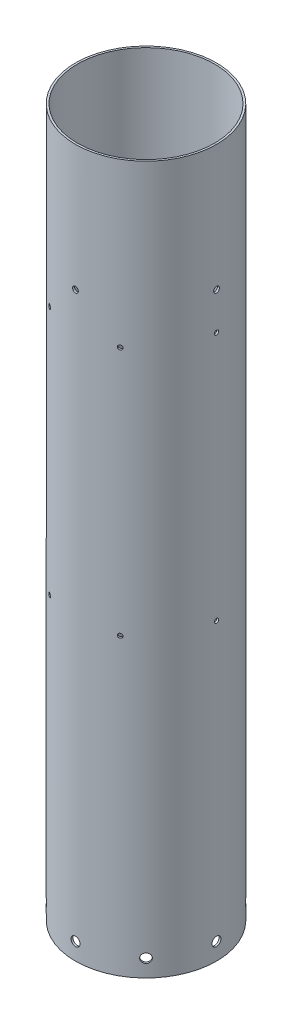
SolidWorks part; units mm, degrees
material "A-Glass Fiber"
ref_plane "Front Plane" through (0, 0, 0) normal (0, 0, 1) x (1, 0, 0)
ref_plane "Top Plane" through (0, 0, 0) normal (0, 1, 0) x (1, 0, 0)
ref_plane "Right Plane" through (0, 0, 0) normal (1, 0, 0) x (0, 0, -1)
sketch "Sketch2" plane through (0, 0, 0) normal (0, 1, 0) x (1, 0, 0)
  circle A0 centre (0, 0) radius 76.2
  circle A1 centre (0, 0) radius 78.359
  dimension "D1" = 156.718
  dimension "D2" = 2.159
extrude "Boss-Extrude1" add sketch "Sketch2" along normal blind 785.495
sketch "Sketch3" plane through (0, 127, 0) normal (1, 0, 0) x (0, 0, -1)
  circle A0 centre (0, -44.45) radius 4.7625 construction
  circle A1 centre (0, -44.45) radius 4.7625 construction
  circle A2 centre (0, -44.45) radius 5.0165
  dimension "D1" = 0.254
extrude "LOX to Kero, LOX Side Holes" [suppressed] cut sketch "Sketch3" along normal up to surface (76.0347 mm away)
pattern_circular "CirPattern1" [suppressed] count 8 over 360
sketch "Sketch4" plane through (0, -25.4, 0) normal (1, 0, 0) x (0, 0, 1)
  circle A0 centre (0, -44.45) radius 4.7625 construction
  circle A1 centre (0, -44.45) radius 4.7625 construction
  circle A2 centre (0, -44.45) radius 5.0165
  dimension "D1" = 0.254
extrude "LOX to Kero, Kero Side Holes" [suppressed] cut sketch "Sketch4" along normal up to surface (76.0347 mm away)
pattern_circular "CirPattern2" [suppressed] count 8 over 360
sketch "Sketch5" plane through (0, -25.4, 0) normal (1, 0, 0) x (0, 0, 1)
  circle A0 centre (0, -44.45) radius 4.7625 construction
  circle A1 centre (0, -44.45) radius 4.7625 construction
  circle A2 centre (0, -44.45) radius 5.0165
  dimension "D1" = 0.254
extrude "N2 to LOX, LOX Side Holes" cut sketch "Sketch5" along normal up to surface (78.1983 mm away)
pattern_circular "CirPattern3" count 8 over 360 about axis through (0, 0, 0) along (0, 1, 0) of "N2 to LOX, LOX Side Holes"
sketch "Sketch7" plane through (0, 0, 0) normal (1, 0, 0) x (0, 0, -1)
  line L0 (-2.3812, 327.3303) -> (2.3812, 327.3303) construction
  line L1 (0, 329.7115) -> (0, 324.949) construction
  line L2 (-2.3812, 604.52) -> (2.3812, 604.52) construction
  line L4 (0, 606.9012) -> (0, 602.1388) construction
  circle A0 centre (0, 604.52) radius 2.3812
  circle A2 centre (0, 327.3303) radius 2.3785
  spline S1 degree 3 poles (-2.3812, 327.3303) (-2.3812, 326.701) (-2.123, 326.0856) (-1.2443, 325.207) (-0.6225, 324.9494) (0.62, 324.9487) (1.2382, 325.2013) (2.1277, 326.0899) (2.381, 326.7078) (2.3815, 327.9511) (2.1241, 328.5729) (1.2467, 329.452) (0.6306, 329.7109) (-0.6258, 329.7122) (-1.2425, 329.4547) (-2.1225, 328.5761) (-2.3813, 327.9596) (-2.3812, 327.3303) (-2.3812, 326.701) (-2.123, 326.0856) knots -0.125 0 0 0 0.125 0.125 0.25 0.25 0.375 0.375 0.5 0.5 0.625 0.625 0.75 0.75 0.875 0.875 1 1 1 1.125 1.125 1.25 only from (-2.3812, 327.3303) to (-2.3812, 327.3303) construction
  spline S2 degree 3 poles (-2.3812, 327.3303) (-2.3812, 326.701) (-2.123, 326.0856) (-1.2443, 325.207) (-0.6225, 324.9494) (0.62, 324.9487) (1.2382, 325.2013) (2.1277, 326.0899) (2.381, 326.7078) (2.3815, 327.9511) (2.1241, 328.5729) (1.2467, 329.452) (0.6306, 329.7109) (-0.6258, 329.7122) (-1.2425, 329.4547) (-2.1225, 328.5761) (-2.3813, 327.9596) (-2.3812, 327.3303) (-2.3812, 326.701) (-2.123, 326.0856) knots -0.125 0 0 0 0.125 0.125 0.25 0.25 0.375 0.375 0.5 0.5 0.625 0.625 0.75 0.75 0.875 0.875 1 1 1 1.125 1.125 1.25 only from (-2.3812, 327.3303) to (-2.3812, 327.3303) construction
  spline S3 degree 3 poles (-2.3812, 604.52) (-2.3812, 603.8907) (-2.123, 603.2754) (-1.2443, 602.3967) (-0.6225, 602.1391) (0.62, 602.1384) (1.2382, 602.391) (2.1277, 603.2797) (2.381, 603.8975) (2.3815, 605.1408) (2.1241, 605.7626) (1.2467, 606.6417) (0.6306, 606.9006) (-0.6258, 606.9019) (-1.2425, 606.6444) (-2.1225, 605.7658) (-2.3813, 605.1493) (-2.3812, 604.52) (-2.3812, 603.8907) (-2.123, 603.2754) knots -0.125 0 0 0 0.125 0.125 0.25 0.25 0.375 0.375 0.5 0.5 0.625 0.625 0.75 0.75 0.875 0.875 1 1 1 1.125 1.125 1.25 only from (-2.3812, 604.52) to (-2.3812, 604.52) construction
  point P8 (0, 327.3303)
  point P17 (0, 604.52)
extrude "Cut-Extrude2" cut sketch "Sketch7" against normal through all both and the other way through all
pattern_circular "CirPattern4" count 4 over 180 about axis through (0, 785.495, 0) along (0, -1, 0) of "Cut-Extrude2"
sketch "Sketch9" plane through (0, 0, 0) normal (1, 0, 0) x (0, 0, -1)
  line L0 (0, 785.495) -> (0, 633.095) construction
  line L1 (76.2, 785.495) -> (-76.2, 785.495) construction
  circle A0 centre (0, 645.795) radius 3.175
  dimension "D3" = 6.35
  dimension "D1" = 152.4
  dimension "D2" = 12.7
extrude "Cut-Extrude3" cut sketch "Sketch9" against normal through all both and the other way through all contours A0
pattern_circular "CirPattern5" count 3 over 180 about axis through (0, 785.495, 0) along (0, -1, 0) of "Cut-Extrude3"
